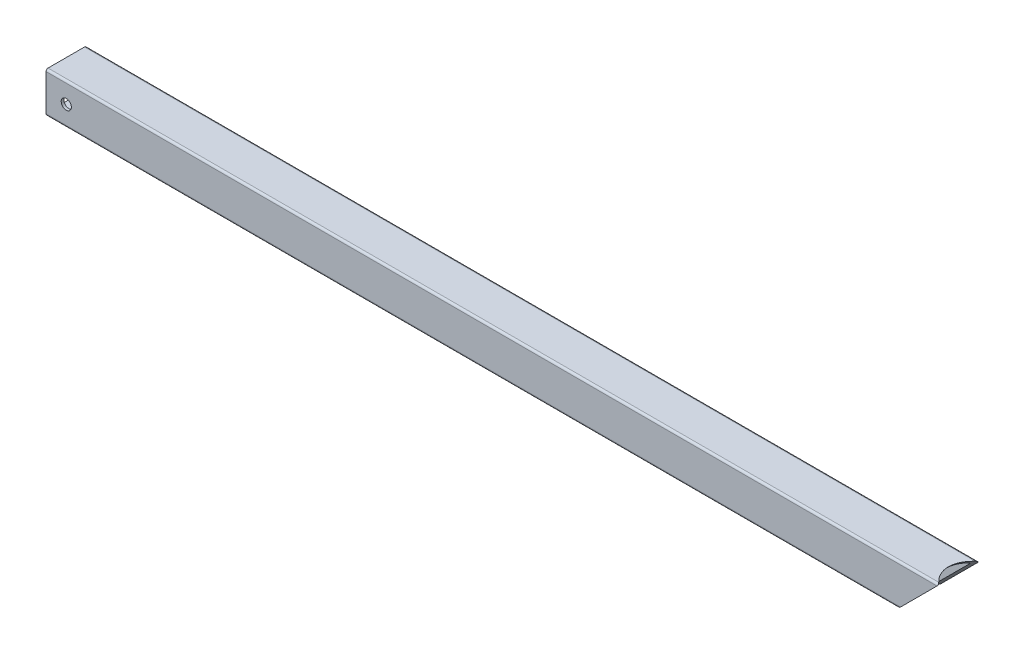
SolidWorks part; units mm, degrees
ref_plane "Front" through (0, 0, 0) normal (0, 0, 1) x (1, 0, 0)
ref_plane "Top" through (0, 0, 0) normal (0, 1, 0) x (1, 0, 0)
ref_plane "Right" through (0, 0, 0) normal (1, 0, 0) x (0, 0, -1)
sketch "Sketch1" plane through (0, 0, 0) normal (1, 0, 0) x (0, 0, -1)
  line L0 (-11.049, 0) -> (-12.7, 0) construction
  line L1 (11.43, -12.7) -> (-11.43, -12.7) construction
  line L2 (12.7, -11.43) -> (12.7, 11.43) construction
  line L3 (11.43, 12.7) -> (-11.43, 12.7) construction
  line L4 (-12.7, -11.43) -> (-12.7, 11.43) construction
  line L5 (12.7, -12.7) -> (-12.7, 12.7) construction
  line L6 (12.7, 12.7) -> (-12.7, -12.7) construction
  line L7 (9.9441, 11.049) -> (-9.9441, 11.049) construction
  line L8 (11.049, 9.9441) -> (11.049, -9.9441) construction
  line L9 (9.9441, -11.049) -> (-9.9441, -11.049) construction
  line L10 (-11.049, 9.9441) -> (-11.049, -9.9441) construction
  line L11 (11.049, 11.049) -> (-11.049, -11.049) construction
  line L12 (11.049, -11.049) -> (-11.049, 11.049) construction
  line L13 (0, -11.049) -> (0, -12.7) construction
  line L14 (11.049, -9.9441) -> (11.049, -12.7) construction
  line L15 (11.049, 0) -> (12.7, 0) construction
  line L16 (11.049, -12.7) -> (12.7, -12.7) construction
  arc A0 (-9.9441, -11.049) -> (-11.049, -9.9441) centre (-9.9441, -9.9441) cw construction
  arc A1 (11.049, -9.9441) -> (9.9441, -11.049) centre (9.9441, -9.9441) cw construction
  arc A2 (9.9441, 11.049) -> (11.049, 9.9441) centre (9.9441, 9.9441) cw construction
  arc A3 (-9.9441, 11.049) -> (-11.049, 9.9441) centre (-9.9441, 9.9441) ccw construction
  arc A4 (11.43, -12.7) -> (12.7, -11.43) centre (11.43, -11.43) ccw construction
  arc A5 (12.7, 11.43) -> (11.43, 12.7) centre (11.43, 11.43) ccw construction
  arc A6 (-11.43, 12.7) -> (-12.7, 11.43) centre (-11.43, 11.43) ccw construction
  arc A7 (-11.43, -12.7) -> (-12.7, -11.43) centre (-11.43, -11.43) cw construction
  point P0 (0, 0)
  point P6 (0, 0)
  dimension "D2" = 1.1049
  dimension "D3" = 1.27
  dimension "Outside Width" = 25.4
  dimension "Ouside Height" = 25.4
  dimension "Inside Height" = 22.098
  dimension "Wall Thickness" = 1.651
sketch "Sketch2" plane through (0, 0, 0) normal (0, 0, 1) x (1, 0, 0)
  line L0 (-279.4, 0) -> (279.4, 0) construction
  point P3 (-255.651, 0)
  point P4 (255.651, 0)
  dimension "Length" = 558.8
  dimension "D1" = 23.749
  dimension "D2" = 23.749
sketch "Sketch4" plane through (0, 0, 0) normal (1, 0, 0) x (0, 0, -1)
  line L8 (12.7, -11.43) -> (12.7, 11.43)
  line L9 (11.43, 12.7) -> (-11.43, 12.7)
  line L10 (-12.7, -11.43) -> (-12.7, 11.43)
  line L11 (11.43, -12.7) -> (-11.43, -12.7)
  line L12 (11.049, 9.9441) -> (11.049, -9.9441)
  line L13 (9.9441, -11.049) -> (-9.9441, -11.049)
  line L14 (-11.049, 9.9441) -> (-11.049, -9.9441)
  line L15 (9.9441, 11.049) -> (-9.9441, 11.049)
  arc A8 (12.7, 11.43) -> (11.43, 12.7) centre (11.43, 11.43) ccw
  arc A9 (-11.43, 12.7) -> (-12.7, 11.43) centre (-11.43, 11.43) ccw
  arc A10 (-12.7, -11.43) -> (-11.43, -12.7) centre (-11.43, -11.43) ccw
  arc A11 (11.43, -12.7) -> (12.7, -11.43) centre (11.43, -11.43) ccw
  arc A12 (9.9441, -11.049) -> (11.049, -9.9441) centre (9.9441, -9.9441) ccw
  arc A13 (-11.049, -9.9441) -> (-9.9441, -11.049) centre (-9.9441, -9.9441) ccw
  arc A14 (-9.9441, 11.049) -> (-11.049, 9.9441) centre (-9.9441, 9.9441) ccw
  arc A15 (11.049, 9.9441) -> (9.9441, 11.049) centre (9.9441, 9.9441) ccw
extrude "Boss-Extrude1" add sketch "Sketch4" along normal up to vertex (279.4 mm away) and the other way up to vertex (279.4 mm away)
sketch "Sketch5" plane through (0, 0, 12.7) normal (0, 0, 1) x (1, 0, 0)
  line L0 (279.4, 12.7) -> (-279.4, 12.7) construction
  line L1 (-279.4, 11.43) -> (-279.4, -11.43) construction
  circle A0 centre (-266.7, 0) radius 3.175
  dimension "D1" = 12.7
  dimension "D2" = 12.7
  dimension "D3" = 6.35
extrude "Cut-Extrude1" cut sketch "Sketch5" against normal through all
ref_plane "Plane1" through (146.05, 146.05, 0) normal (0.7071, 0.7071, 0) x (0, 0, 1)
sketch "Sketch6" plane through (146.05, 146.05, 0) normal (0.7071, 0.7071, 0) x (0, 0, 1)
  line L1 (11.43, 206.5459) -> (-11.43, 206.5459) construction
  line L2 (-12.7, 205.6479) -> (-12.7, 189.4834) construction
  circle A0 centre (0, 203.2439) radius 19.05
  dimension "D1" = 38.1
  dimension "D2" = 3.302
  dimension "D3" = 12.7
extrude "Cut-Extrude2" cut sketch "Sketch6" against normal through all
equation "\"D3@Sketch1\"=\"Outside Width@Sketch1\"*.05"
equation "\"D2@Sketch1\" = \"Inside Height@Sketch1\" * .05"
equation "\"D1@Sketch2\"=\"Outside Width@Sketch1\"-\"Wall Thickness@Sketch1\""
equation "\"D2@Sketch2\"=\"D1@Sketch2\""
